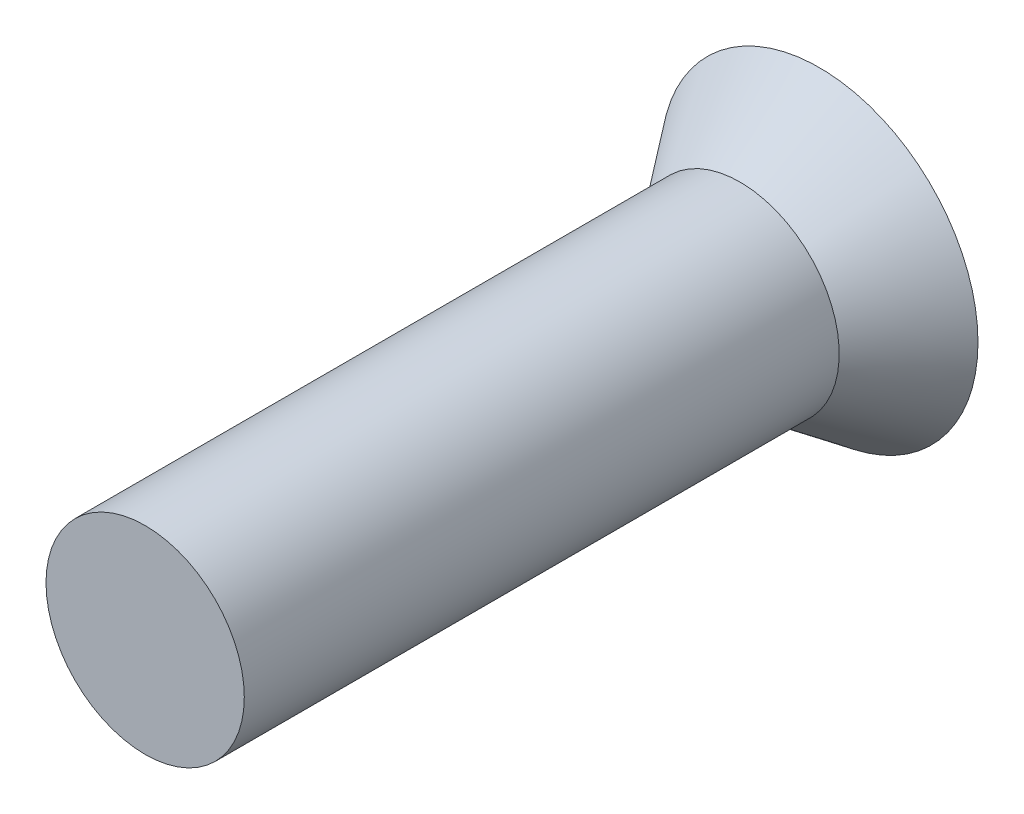
SolidWorks part; units mm, degrees
material "6063-T5"
ref_plane "Front Plane" through (0, 0, 0) normal (1, 0, 0) x (0, 1, 0)
ref_plane "Top Plane" through (0, 0, 0) normal (0, 0, 1) x (0, 1, 0)
ref_plane "Right Plane" through (0, 0, 0) normal (0, 1, 0) x (-1, 0, 0)
sketch "Sketch1" plane through (0, 0, 0) normal (0, 0, 1) x (0, 1, 0)
  circle A0 centre (0, 0) radius 4
  dimension "D1" = 8
extrude "Boss-Extrude1" add sketch "Sketch1" along normal blind 2
sketch "Sketch2" plane through (0, 0, 2) normal (0, 0, 1) x (1, 0, 0)
  circle A0 centre (0, 0) radius 2.5
  dimension "D1" = 5
extrude "Boss-Extrude2" add sketch "Sketch2" along normal blind 15
sketch "Sketch3" plane through (0, 0, 0) normal (1, 0, 0) x (0, 1, 0)
  line L5 (-2.5, 2) -> (-4, 2)
  line L6 (4, 2) -> (-4, 2) construction
  line L7 (-4, 2) -> (-4, 0)
  line L8 (-4, 0) -> (-2.5, 2)
  line L9 (0, 0) -> (0, 2) construction
revolve "Cut-Revolve1" cut sketch "Sketch3" angle 360 about L9
